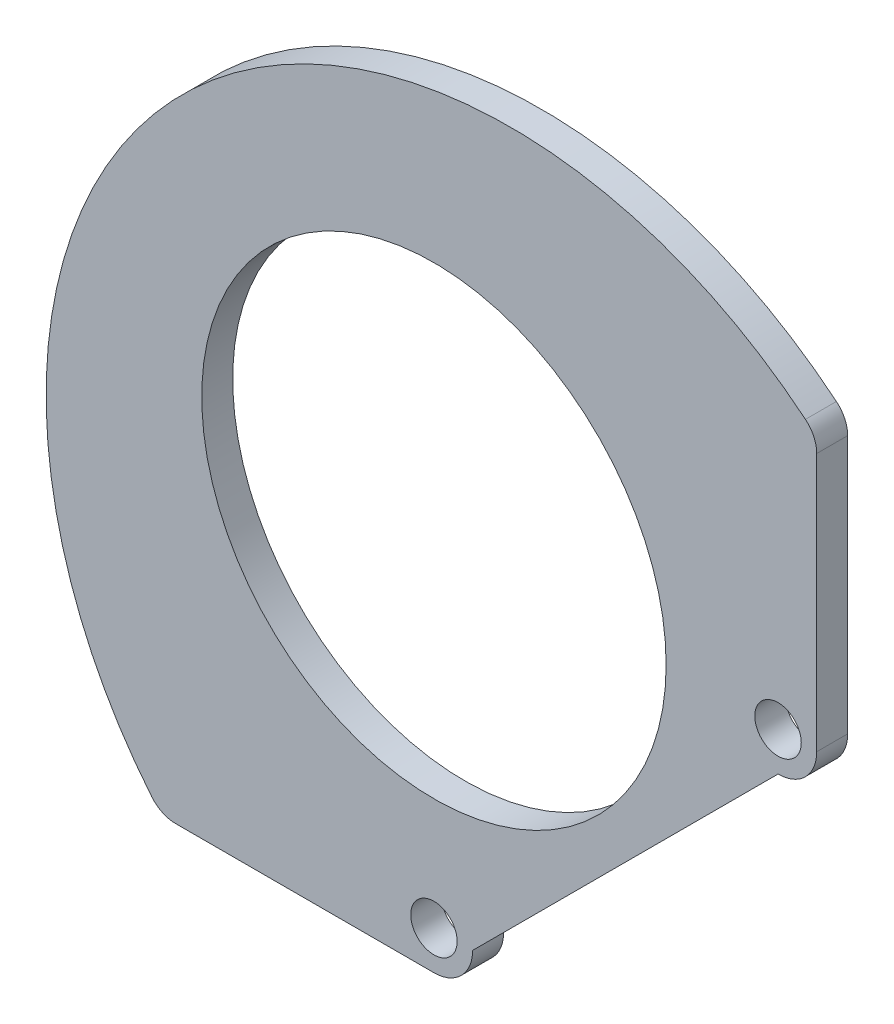
SolidWorks part; units mm, degrees
ref_plane "前视基准面" through (0, 0, 0) normal (0, 0, 1) x (1, 0, 0)
ref_plane "上视基准面" through (0, 0, 0) normal (0, 1, 0) x (1, 0, 0)
ref_plane "右视基准面" through (0, 0, 0) normal (1, 0, 0) x (0, 0, -1)
sketch "Sketch1" plane through (0, 0, 0) normal (0, 0, 1) x (1, 0, 0)
  line L0 (30, 0) -> (0, -30) construction
  line L1 (22.4516, -22.4516) -> (-21.2132, 21.2132) construction
  line L2 (-4.9497, -10.0503) -> (-4.9497, -24.5051) construction
  line L3 (10.0503, 4.9497) -> (24.5051, 4.9497) construction
  line L4 (-2.4497, -17.2777) -> (17.2777, 2.4497)
  line L5 (19.7777, 4.9497) -> (19.7777, 22.5576)
  line L6 (-4.9497, -19.7777) -> (-22.5576, -19.7777)
  arc A0 (19.7777, 22.5576) -> (-22.5576, -19.7777) centre (0, 0) ccw
  circle A1 centre (-4.9497, 4.9497) radius 15
  circle A2 centre (0, 0) radius 25 construction
  circle A7 centre (17.2777, 4.9497) radius 1.5
  circle A8 centre (-4.9497, -17.2777) radius 1.5
  circle A9 centre (-4.9497, -17.2777) radius 2.5
  circle A10 centre (17.2777, 4.9497) radius 2.5
  dimension "D1" = 23
  dimension "D2" = 60
  dimension "D3" = 30
  dimension "D4" = 1
  dimension "D6" = 50
  dimension "D5" = 1
extrude "Boss-Extrude1" add sketch "Sketch1" along normal blind 2
fillet "Fillet1" radius 2 2 edges at (19.7777, 22.5576, 1) (-22.5576, -19.7777, 1)
